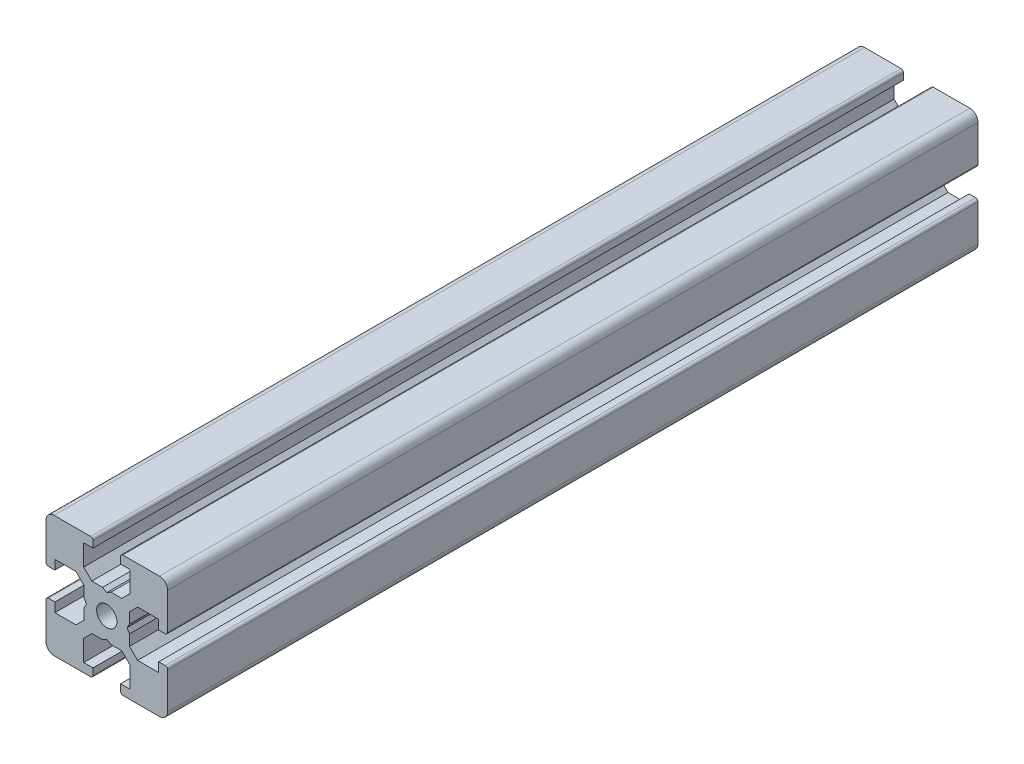
SolidWorks part; units mm, degrees
ref_plane "Front" through (0, 0, 0) normal (0, 0, 1) x (1, 0, 0)
ref_plane "Top" through (0, 0, 0) normal (0, 1, 0) x (1, 0, 0)
ref_plane "Right" through (0, 0, 0) normal (1, 0, 0) x (0, 0, -1)
ref_plane "Plane1" through (0, 0, 115) normal (0, 0, 1) x (1, 0, 0)
sketch "Sketch1" plane through (0, 0, 115) normal (0, 0, 1) x (1, 0, 0)
  line L0 (-7.5, 6.5) -> (-7.5, 2)
  line L1 (-7.2, 1.7) -> (-6.4, 1.7)
  line L2 (-6.4, 1.7) -> (-6.4, 2.85)
  line L3 (-6.4, 2.85) -> (-3.8, 2.85)
  line L4 (-3.8, 2.85) -> (-2.8, 1.85)
  line L5 (-2.8, 1.85) -> (-2.8, 0.5196)
  line L6 (-2.8, 0.5196) -> (-2.5, 0)
  line L7 (-2.5, 0) -> (-2.8, -0.5196)
  line L8 (-2.8, -0.5196) -> (-2.8, -1.85)
  line L9 (-2.8, -1.85) -> (-3.8, -2.85)
  line L10 (-3.8, -2.85) -> (-6.4, -2.85)
  line L11 (-6.4, -2.85) -> (-6.4, -1.7)
  line L12 (-6.4, -1.7) -> (-7.2, -1.7)
  line L13 (-7.5, -2) -> (-7.5, -6.5)
  line L14 (-6.5, -7.5) -> (-2, -7.5)
  line L15 (-1.7, -7.2) -> (-1.7, -6.4)
  line L16 (-1.7, -6.4) -> (-2.85, -6.4)
  line L17 (-2.85, -6.4) -> (-2.85, -3.8)
  line L18 (-2.85, -3.8) -> (-1.85, -2.8)
  line L19 (-1.85, -2.8) -> (-0.5196, -2.8)
  line L20 (-0.5196, -2.8) -> (0, -2.5)
  line L21 (0, -2.5) -> (0.5196, -2.8)
  line L22 (0.5196, -2.8) -> (1.85, -2.8)
  line L23 (1.85, -2.8) -> (2.85, -3.8)
  line L24 (2.85, -3.8) -> (2.85, -6.4)
  line L25 (2.85, -6.4) -> (1.7, -6.4)
  line L26 (1.7, -6.4) -> (1.7, -7.2)
  line L27 (2, -7.5) -> (6.5, -7.5)
  line L28 (7.5, -6.5) -> (7.5, -2)
  line L29 (7.2, -1.7) -> (6.4, -1.7)
  line L30 (6.4, -1.7) -> (6.4, -2.85)
  line L31 (6.4, -2.85) -> (3.8, -2.85)
  line L32 (3.8, -2.85) -> (2.8, -1.85)
  line L33 (2.8, -1.85) -> (2.8, -0.5196)
  line L34 (2.8, -0.5196) -> (2.5, 0)
  line L35 (2.5, 0) -> (2.8, 0.5196)
  line L36 (2.8, 0.5196) -> (2.8, 1.85)
  line L37 (2.8, 1.85) -> (3.8, 2.85)
  line L38 (3.8, 2.85) -> (6.4, 2.85)
  line L39 (6.4, 2.85) -> (6.4, 1.7)
  line L40 (6.4, 1.7) -> (7.2, 1.7)
  line L41 (7.5, 2) -> (7.5, 6.5)
  line L42 (6.5, 7.5) -> (2, 7.5)
  line L43 (1.7, 7.2) -> (1.7, 6.4)
  line L44 (1.7, 6.4) -> (2.85, 6.4)
  line L45 (2.85, 6.4) -> (2.85, 3.8)
  line L46 (2.85, 3.8) -> (1.85, 2.8)
  line L47 (1.85, 2.8) -> (0.5196, 2.8)
  line L48 (0.5196, 2.8) -> (0, 2.5)
  line L49 (0, 2.5) -> (-0.5196, 2.8)
  line L50 (-0.5196, 2.8) -> (-1.85, 2.8)
  line L51 (-1.85, 2.8) -> (-2.85, 3.8)
  line L52 (-2.85, 3.8) -> (-2.85, 6.4)
  line L53 (-2.85, 6.4) -> (-1.7, 6.4)
  line L54 (-1.7, 6.4) -> (-1.7, 7.2)
  line L55 (-2, 7.5) -> (-6.5, 7.5)
  circle A0 centre (0, 0) radius 1.25
  arc A1 (-7.5, 2) -> (-7.2, 1.7) centre (-7.2, 2) ccw
  arc A2 (-7.2, -1.7) -> (-7.5, -2) centre (-7.2, -2) ccw
  arc A3 (-7.5, -6.5) -> (-6.5, -7.5) centre (-6.5, -6.5) ccw
  arc A4 (-2, -7.5) -> (-1.7, -7.2) centre (-2, -7.2) ccw
  arc A5 (1.7, -7.2) -> (2, -7.5) centre (2, -7.2) ccw
  arc A6 (6.5, -7.5) -> (7.5, -6.5) centre (6.5, -6.5) ccw
  arc A7 (7.5, -2) -> (7.2, -1.7) centre (7.2, -2) ccw
  arc A8 (7.2, 1.7) -> (7.5, 2) centre (7.2, 2) ccw
  arc A9 (7.5, 6.5) -> (6.5, 7.5) centre (6.5, 6.5) ccw
  arc A10 (2, 7.5) -> (1.7, 7.2) centre (2, 7.2) ccw
  arc A11 (-1.7, 7.2) -> (-2, 7.5) centre (-2, 7.2) ccw
  arc A12 (-6.5, 7.5) -> (-7.5, 6.5) centre (-6.5, 6.5) ccw
extrude "Boss-Extrude1" add sketch "Sketch1" against normal blind 100
